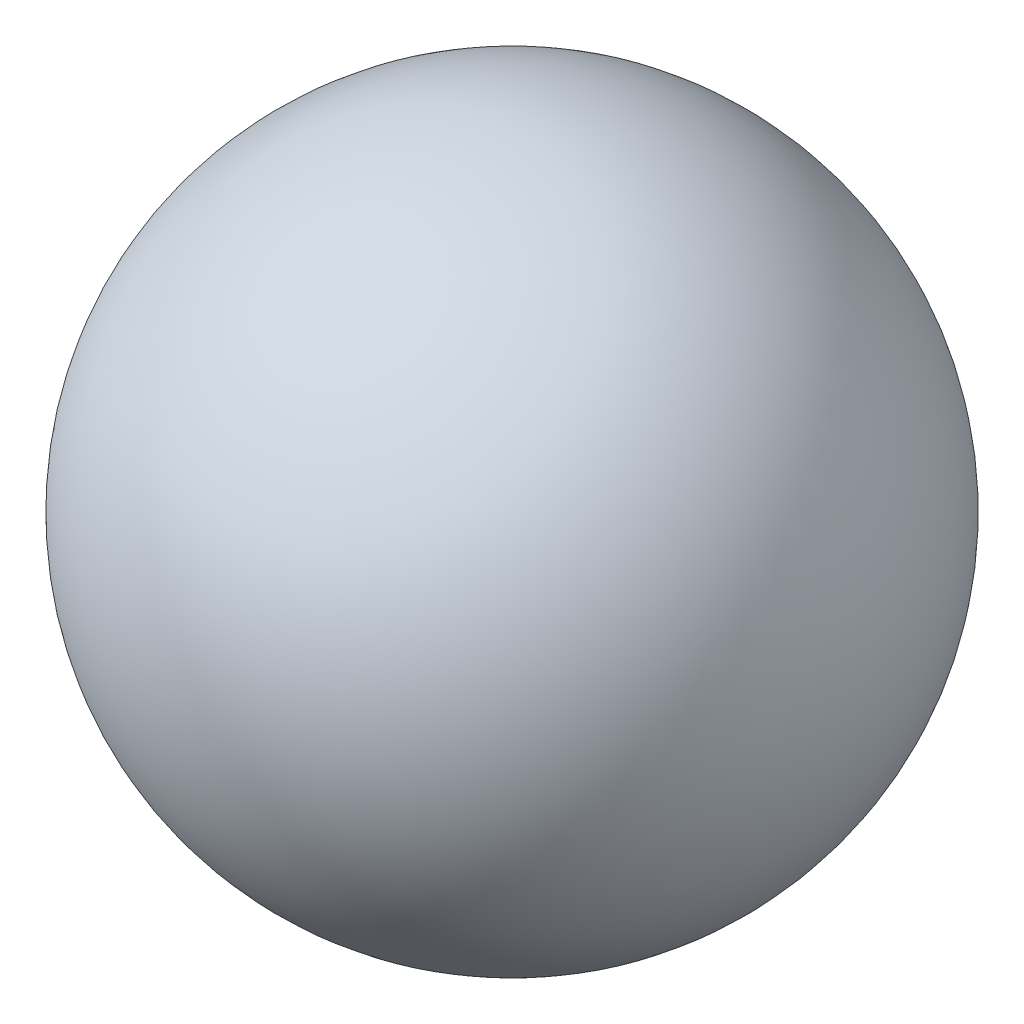
SolidWorks part; units mm, degrees
ref_plane "Front" through (0, 0, 0) normal (0, 0, 1) x (1, 0, 0)
ref_plane "Top" through (0, 0, 0) normal (0, 1, 0) x (1, 0, 0)
ref_plane "Right" through (0, 0, 0) normal (1, 0, 0) x (0, 0, -1)
sketch "Sketch1" plane through (0, 0, 0) normal (0, 0, 1) x (1, 0, 0)
  line L0 (0, 215.9) -> (0, 0)
  arc A0 (0, 0) -> (0, 215.9) centre (0, 107.95) ccw
  dimension "D1" = 215.9
revolve "Revolve1" add sketch "Sketch1" angle 360 about L0
ref_plane "Plane1" through (0, 0, 0) normal (0, 1, 0) x (1, 0, 0)
ref_plane "Mid_Plane" through (0, 107.95, 0) normal (0, 1, 0) x (1, 0, 0)
ref_plane "Ball_Floor" through (107.95, 0, 0) normal (1, 0, 0) x (0, 0, -1)
